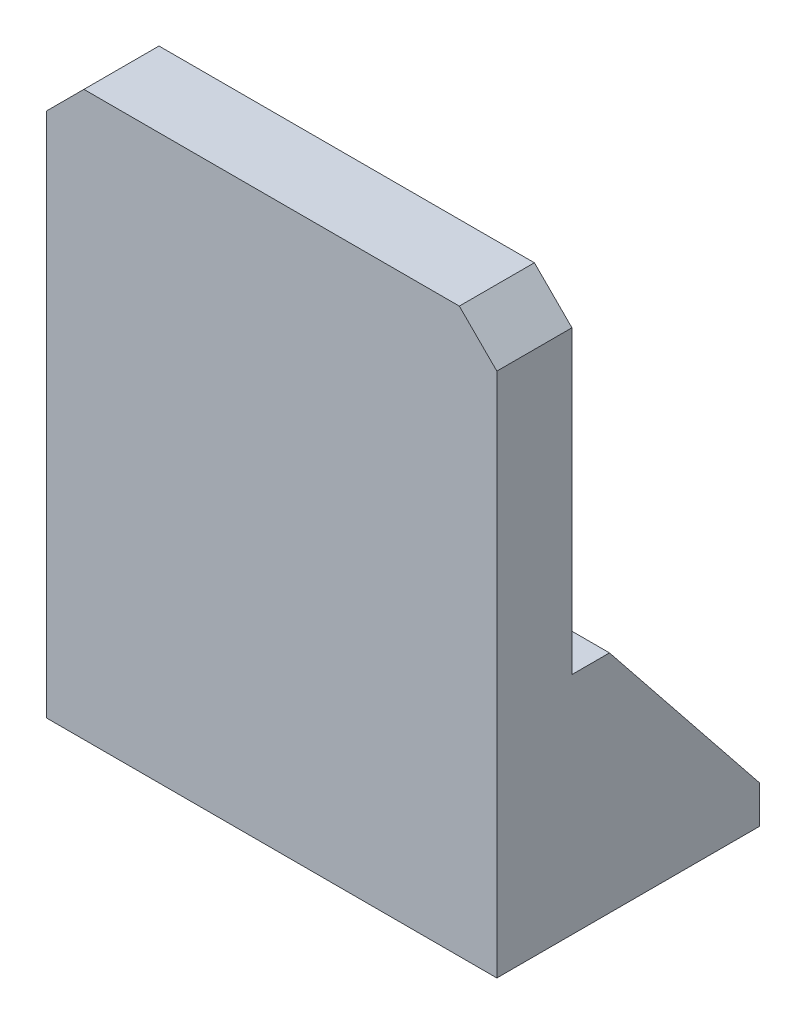
SolidWorks part; units mm, degrees
ref_plane "前视基准面" through (0, 0, 0) normal (0, 0, 1) x (1, 0, 0)
ref_plane "上视基准面" through (0, 0, 0) normal (0, 1, 0) x (1, 0, 0)
ref_plane "右视基准面" through (0, 0, 0) normal (1, 0, 0) x (0, 0, -1)
sketch "草图1" plane through (0, 0, 0) normal (0, 0, 1) x (1, 0, 0)
  line L1 (-60, 75) -> (60, 75)
  line L2 (-60, 75) -> (-60, -75)
  line L3 (-60, -75) -> (60, -75)
  line L4 (60, 75) -> (60, -75)
  line L5 (-60, 75) -> (60, -75) construction
  line L6 (-60, -75) -> (60, 75) construction
  point P0 (0, 0)
  dimension "D1" = 150
  dimension "D2" = 120
extrude "凸台-拉伸1" add sketch "草图1" along normal mid plane 20
chamfer "倒角1" distance 10 angle 45 2 edges at (-60, 75, 0) (60, 75, 0)
sketch "草图2" plane through (60, 0, 0) normal (1, 0, 0) x (0, 0, -1)
  line L0 (10, -75) -> (60, -75)
  line L1 (60, -75) -> (60, -65)
  line L2 (10, -75) -> (10, 65) construction
  line L3 (10, -15) -> (10, -75)
  line L4 (60, -65) -> (20, -15)
  line L5 (20, -15) -> (10, -15)
  dimension "D1" = 50
  dimension "D2" = 60
  dimension "D3" = 10
extrude "凸台-拉伸2" add sketch "草图2" against normal blind 20
mirror "镜向1" about plane through (0, 0, 0) normal (1, 0, 0) of "凸台-拉伸2"
equation "\"零件重量\"= \"SW-质量\""
